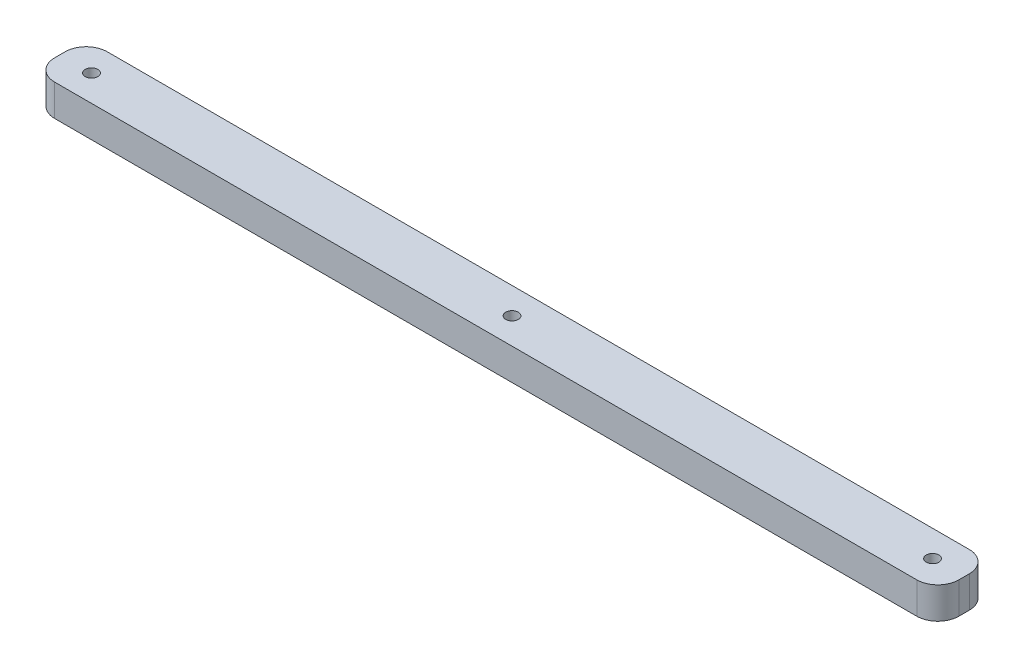
SolidWorks part; units mm, degrees
ref_plane "Front Plane" through (0, 0, 0) normal (0, 0, 1) x (1, 0, 0)
ref_plane "Top Plane" through (0, 0, 0) normal (0, 1, 0) x (1, 0, 0)
ref_plane "Right Plane" through (0, 0, 0) normal (1, 0, 0) x (0, 0, -1)
sketch "Sketch1" plane through (0, 0, 0) normal (0, -1, 0) x (-1, 0, 0)
  line L3 (83, 2.5) -> (3, 2.5) construction
  line L4 (43, 0) -> (43, 2.5) construction
  line L5 (0, 5) -> (86, 5)
  line L6 (0, 5) -> (0, 0)
  line L7 (0, 0) -> (86, 0)
  line L8 (86, 5) -> (86, 0)
  circle A0 centre (83, 2.5) radius 0.6
  circle A1 centre (3, 2.5) radius 0.6
  point P19 (43, 2.5)
  dimension "D2" = 86
  dimension "D3" = 1.2
  dimension "D4" = 80
  dimension "D1" = 5
  dimension "D5" = 2.5
extrude "Boss-Extrude1" add sketch "Sketch1" along normal blind 3 contours L5 L8 L7 L6
fillet "Fillet1" radius 2 4 edges at (0, -1.5, 0) (0, -1.5, -5) (-86, -1.5, -5) (-86, -1.5, 0)
sketch "Sketch3" plane through (0, -3, 0) normal (0, -1, 0) x (1, 0, 0)
  line L3 (-84, -5) -> (-2, -5) construction
  line L4 (-43, 0) -> (-43, -5) construction
  line L5 (-2, 0) -> (-84, 0) construction
  circle A0 centre (-43, -2.5) radius 0.6
  circle A1 centre (-3, -2.5) radius 0.6 construction
  point P9 (-43, -5)
extrude "Cut-Extrude1" cut sketch "Sketch3" against normal up to next
